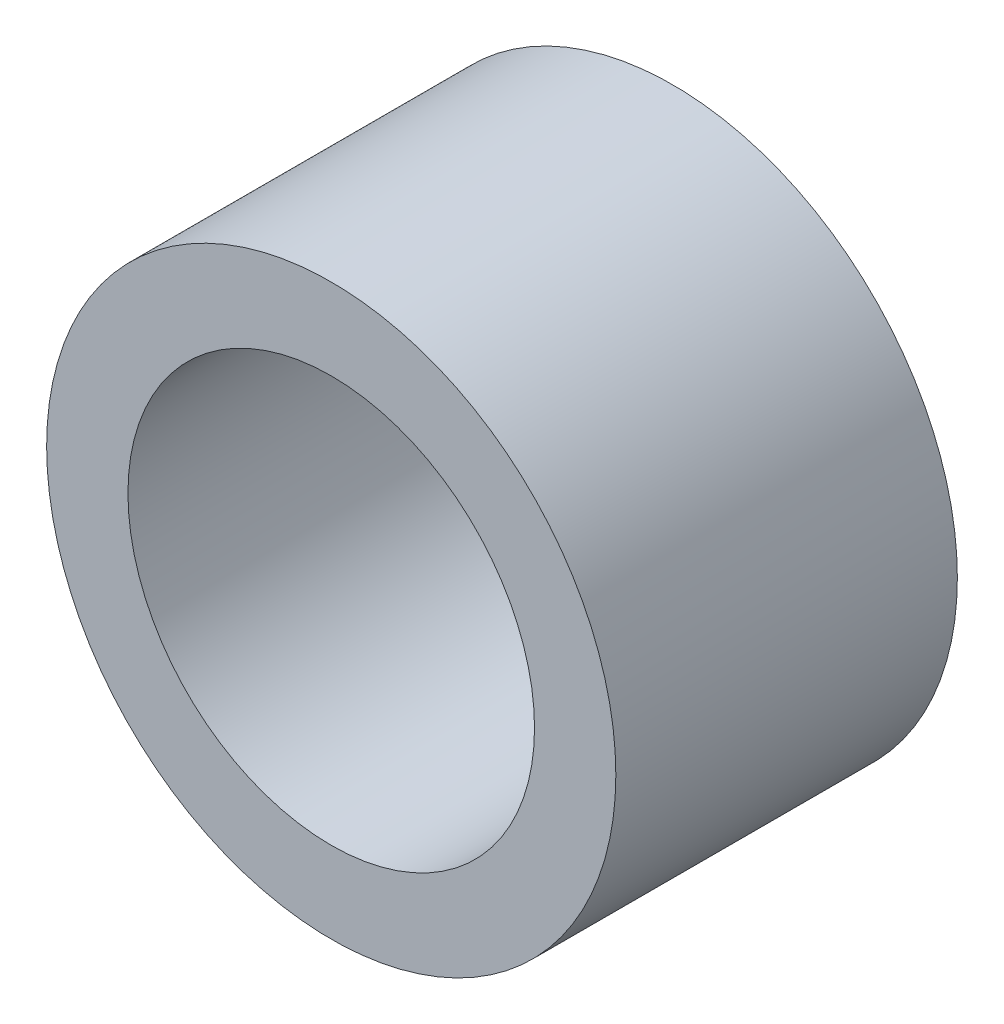
SolidWorks part; units mm, degrees
material "Alloy Steel"
ref_plane "Front Plane" through (0, 0, 0) normal (0, 0, 1) x (1, 0, 0)
ref_plane "Top Plane" through (0, 0, 0) normal (0, 1, 0) x (1, 0, 0)
ref_plane "Right Plane" through (0, 0, 0) normal (1, 0, 0) x (0, 0, -1)
sketch "Sketch1" plane through (0, 0, 0) normal (0, 0, 1) x (1, 0, 0)
  circle A0 centre (0, 0) radius 17.5
  circle A1 centre (0, 0) radius 12.5
  dimension "D1" = 35
  dimension "D2" = 25
extrude "Boss-Extrude1" add sketch "Sketch1" along normal blind 21
